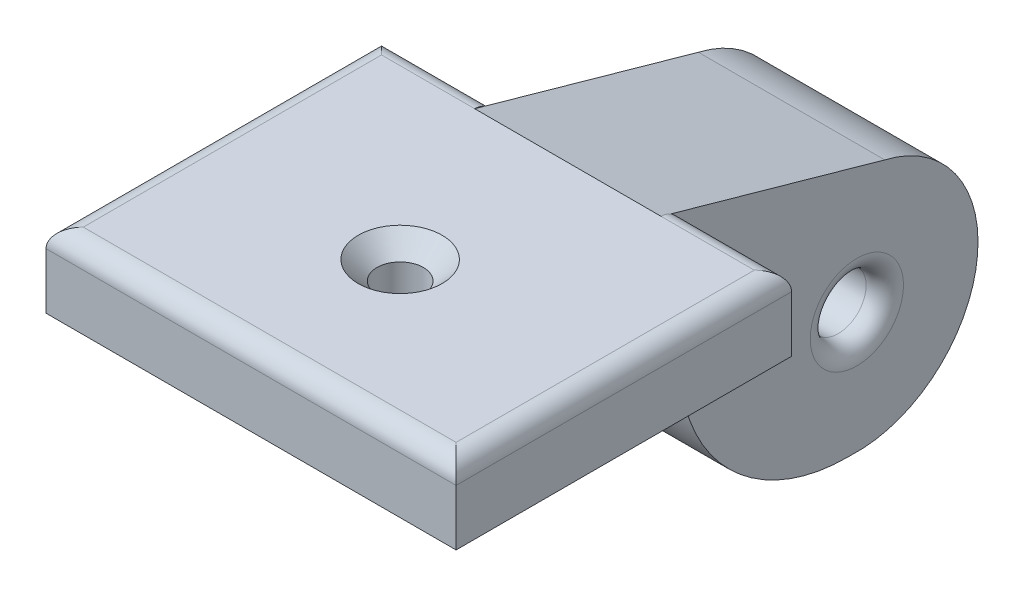
SolidWorks part; units mm, degrees
ref_plane "Front Plane" through (0, 0, 0) normal (0, 0, 1) x (1, 0, 0)
ref_plane "Top Plane" through (0, 0, 0) normal (0, 1, 0) x (1, 0, 0)
ref_plane "Right Plane" through (0, 0, 0) normal (1, 0, 0) x (0, 0, -1)
sketch "Sketch1" plane through (0, 0, 0) normal (0, 1, 0) x (1, 0, 0)
  line L1 (-8.2409, 25.3577) -> (2.7591, 25.3577)
  line L2 (-8.2409, 25.3577) -> (-8.2409, 7.3577)
  line L3 (-8.2409, 7.3577) -> (2.7591, 7.3577)
  line L4 (2.7591, 25.3577) -> (2.7591, 7.3577)
  line L5 (-8.2409, 25.3577) -> (-3.2409, 25.3577)
  line L6 (-8.2409, 25.3577) -> (-8.2409, 36.3577)
  line L7 (-8.2409, 36.3577) -> (-3.2409, 36.3577)
  line L8 (-3.2409, 25.3577) -> (-3.2409, 36.3577)
  dimension "D1" = 18
  dimension "D2" = 11
  dimension "D3" = 6
  dimension "D4" = 11
extrude "Boss-Extrude1" add sketch "Sketch1" along normal blind 4 contours L4 L1 L2 L3 | L1 L8 L7 L6
sketch "Sketch2" plane through (-3.2409, 0, 0) normal (1, 0, 0) x (0, 0, -1)
  line L0 (36.3577, 4) -> (36.3577, 0) construction
  line L1 (25.3577, 0) -> (34.5379, 0)
  line L2 (25.3577, 0) -> (25.3577, -12.1921)
  line L3 (25.3577, -12.1921) -> (34.5379, -12.1921)
  line L4 (34.5379, 0) -> (34.5379, -12.1921)
  circle A0 centre (34.8577, -5.7) radius 1.5
  arc A1 (34.5379, -12.1921) -> (36.3577, 0.6246) centre (34.8577, -5.7) ccw
  line M6 (25.3577, 0) -> (36.3577, 0)
  line M7 (36.3577, 0) -> (36.3577, 4)
  dimension "D2" = 9.5
  dimension "D1" = 5.7
extrude "Boss-Extrude2" add sketch "Sketch2" against normal blind 5 contours A0 L4 L2 L3 M6 | L4 A1 A0 M7 M6
mirror "Mirror1" about plane through (-8.2409, 4, 0) normal (1, 0, 0) of "Boss-Extrude2", "Boss-Extrude1"
sketch "Sketch3" plane through (0, 4, 0) normal (0, 1, 0) x (1, 0, 0)
  line L0 (-8.2409, 41.3577) -> (-8.2409, 7.0572) construction
  line L1 (-3.2409, 41.3577) -> (-13.2409, 41.3577) construction
  line L2 (2.7591, 25.3577) -> (2.7591, 7.3577) construction
  line L3 (-3.2409, 25.3577) -> (2.7591, 25.3577) construction
  circle A0 centre (-8.2409, 15.3577) radius 1.2484
  point P6 (-7.2409, 15.3577)
  dimension "D1" = 11
  dimension "D2" = 10
extrude "Cut-Extrude1" cut sketch "Sketch3" against normal blind 5
fillet "Fillet1" radius 1 7 edges at (-0.2409, 4, -25.3577) (2.7591, 4, -16.3577) (-8.2409, 4, -7.3577) (-16.2409, 4, -25.3577) (-19.2409, 4, -16.3577) (-13.2409, -5.7, -36.3577) (-3.2409, -5.7, -36.3577)
fillet "Fillet3" radius 2 1 edges at (-8.2409, 0, -25.3577)
fillet "Fillet4" radius 9 1 edges at (-8.2409, -12.1921, -25.3577)
sketch "Sketch4" plane through (-13.2409, 0, 0) normal (-1, 0, 0) x (0, 0, 1)
  line L0 (-36.3577, 0.6246) -> (-24.3577, 4)
  line L1 (-36.3577, 4) -> (-36.3577, 0.6246) construction
  line L2 (-36.3577, 0.6246) -> (-36.3577, 4)
  line L4 (-36.3577, 4) -> (-24.3577, 4)
extrude "Cut-Extrude2" cut sketch "Sketch4" against normal blind 10
chamfer "Chamfer2" distance 1 angle 45 1 edges at (-8.2409, 4, -14.1092)
equation "\"7cmmm\"=6.5"
